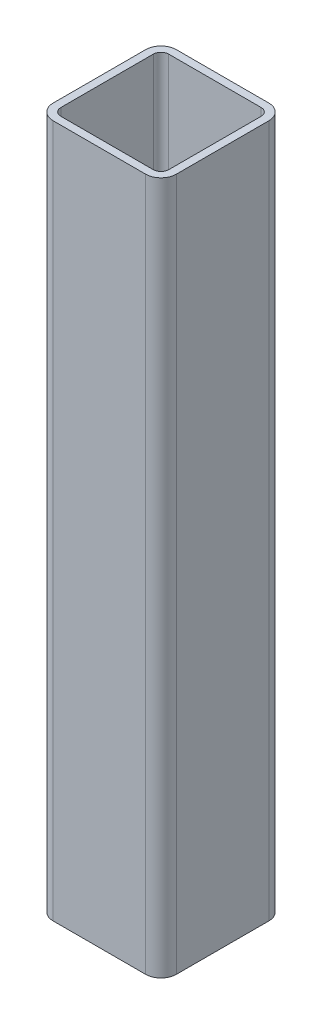
SolidWorks part; units mm, degrees
material "1.0037 (S235JR)"
ref_plane "Płaszczyzna przednia" through (0, 0, 0) normal (0, 0, 1) x (1, 0, 0)
ref_plane "Płaszczyzna górna" through (0, 0, 0) normal (0, 1, 0) x (1, 0, 0)
ref_plane "Płaszczyzna prawa" through (0, 0, 0) normal (1, 0, 0) x (0, 0, -1)
sketch "Szkic1" plane through (0, 0, 0) normal (0, 1, 0) x (1, 0, 0)
  line L0 (5, 10) -> (5, 70)
  line L1 (10, 0) -> (70, 0)
  line L2 (0, 10) -> (0, 70)
  line L3 (10, 80) -> (70, 80)
  line L4 (80, 10) -> (80, 70)
  line L5 (10, 75) -> (70, 75)
  line L6 (75, 10) -> (75, 70)
  line L7 (10, 5) -> (70, 5)
  arc A0 (70, 0) -> (80, 10) centre (70, 10) ccw
  arc A1 (80, 70) -> (70, 80) centre (70, 70) ccw
  arc A2 (10, 80) -> (0, 70) centre (10, 70) ccw
  arc A3 (0, 10) -> (10, 0) centre (10, 10) ccw
  arc A4 (10, 75) -> (5, 70) centre (10, 70) ccw
  arc A5 (75, 70) -> (70, 75) centre (70, 70) ccw
  arc A6 (70, 5) -> (75, 10) centre (70, 10) ccw
  arc A7 (5, 10) -> (10, 5) centre (10, 10) ccw
  dimension "D2" = 10
  dimension "D1" = 80
  dimension "D3" = 5
extrude "Dodanie-wyciągnięcie1" add sketch "Szkic1" along normal blind 450
